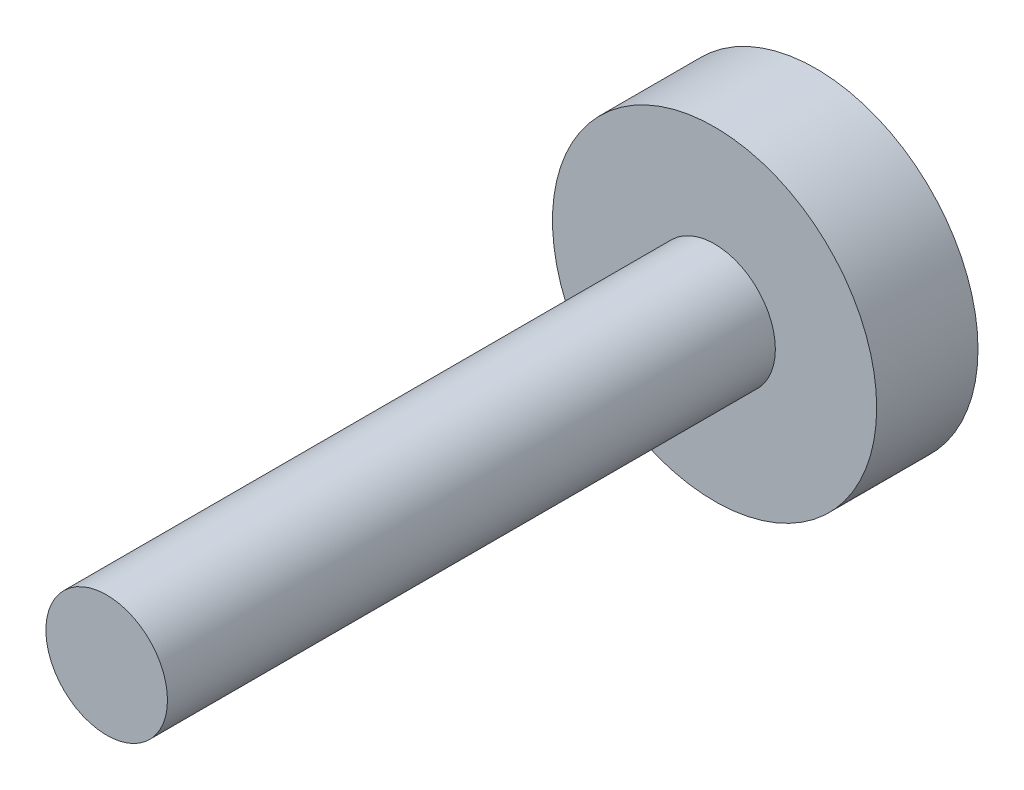
SolidWorks part; units mm, degrees
ref_plane "Front Plane" through (0, 0, 0) normal (0, 0, 1) x (1, 0, 0)
ref_plane "Top Plane" through (0, 0, 0) normal (0, 1, 0) x (1, 0, 0)
ref_plane "Right Plane" through (0, 0, 0) normal (1, 0, 0) x (0, 0, -1)
sketch "Sketch1" plane through (0, 0, 0) normal (0, 0, 1) x (1, 0, 0)
  circle A0 centre (0, 0) radius 4
extrude "Boss-Extrude1" add sketch "Sketch1" along normal blind 2.5
sketch "Sketch2" plane through (0, 0, 2.5) normal (0, 0, 1) x (1, 0, 0)
  circle A0 centre (0, 0) radius 1.5
  dimension "D1" = 3
extrude "Boss-Extrude2" add sketch "Sketch2" along normal blind 15
